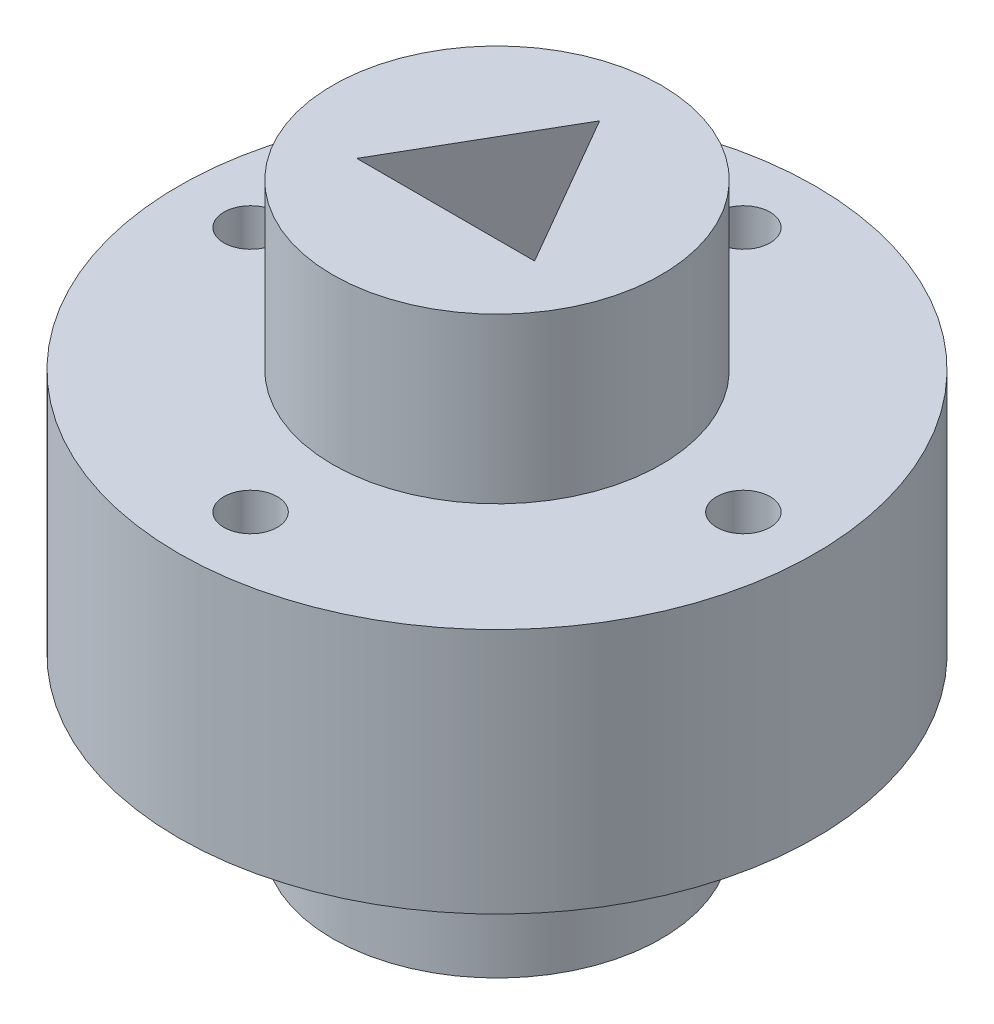
SolidWorks part; units mm, degrees
ref_plane "Front" through (0, 0, 0) normal (0, 0, 1) x (1, 0, 0)
ref_plane "Top" through (0, 0, 0) normal (0, 1, 0) x (1, 0, 0)
ref_plane "Right" through (0, 0, 0) normal (1, 0, 0) x (0, 0, -1)
sketch "Sketch1" plane through (0, 0, 0) normal (0, 1, 0) x (1, 0, 0)
  circle A0 centre (0, 0) radius 4
  dimension "D1" = 8
extrude "Boss-Extrude1" add sketch "Sketch1" along normal blind 4
sketch "Sketch2" plane through (0, 4, 0) normal (0, 1, 0) x (1, 0, 0)
  circle A0 centre (0, 6) radius 0.65
  circle A1 centre (6, 0) radius 0.65
  circle A2 centre (0, -6) radius 0.65
  circle A3 centre (-6, 0) radius 0.65
  circle A4 centre (0, 0) radius 7.75
  point P4 (0, 0)
  point P8 (0, 0)
  dimension "D3" = 4
  dimension "D1" = 15.5
extrude "Boss-Extrude2" add sketch "Sketch2" along normal blind 6
sketch "Sketch3" plane through (0, 10, 0) normal (0, 1, 0) x (1, 0, 0)
  circle A0 centre (0, 0) radius 4
extrude "Boss-Extrude3" add sketch "Sketch3" along normal blind 4
sketch "Sketch4" plane through (0, 14, 0) normal (0, 1, 0) x (1, 0, 0)
  line L0 (0, 2.5) -> (-2.1651, -1.25)
  line L1 (-2.1651, -1.25) -> (2.1651, -1.25)
  line L2 (0, 2.5) -> (2.1651, -1.25)
  circle A0 centre (0, 0) radius 2.5
  dimension "D1" = 5
  dimension "D2" = 60
extrude "Cut-Extrude1" cut sketch "Sketch4" against normal blind 24 contours L2 L0 L1
